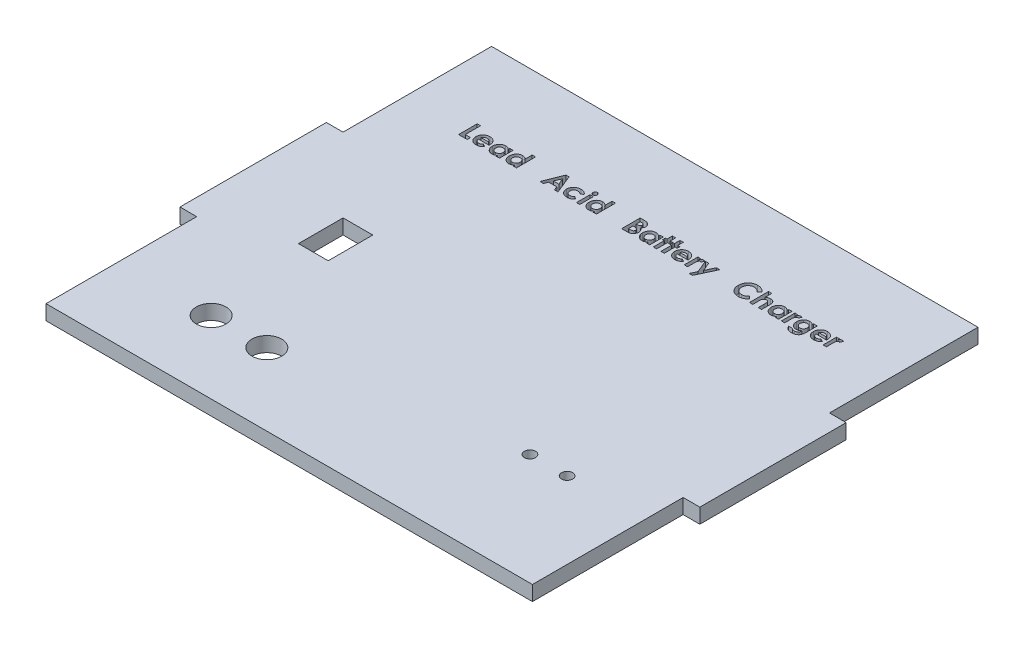
SolidWorks part; units mm, degrees
ref_plane "Front Plane" through (0, 0, 0) normal (0, 0, 1) x (1, 0, 0)
ref_plane "Top Plane" through (0, 0, 0) normal (0, 1, 0) x (1, 0, 0)
ref_plane "Right Plane" through (0, 0, 0) normal (1, 0, 0) x (0, 0, -1)
sketch "Sketch1" plane through (0, 0, 0) normal (0, 1, 0) x (1, 0, 0)
  line L0 (-65.5, 20) -> (-70, 20)
  line L1 (-65.5, -60) -> (65.5, -60)
  line L2 (-65.5, -60) -> (-65.5, -19.4155)
  line L3 (-65.5, 60) -> (65.5, 60)
  line L4 (65.5, -60) -> (65.5, -19.4155)
  line L5 (-65.5, -60) -> (65.5, 60) construction
  line L6 (-65.5, 60) -> (65.5, -60) construction
  line L7 (-70, 20) -> (-70, -19.4155)
  line L8 (-70, -19.4155) -> (-65.5, -19.4155)
  line L9 (-65.5, 20) -> (-65.5, 60)
  line L10 (0, 68.2418) -> (0, -80.8901) construction
  line L11 (70, -19.4155) -> (65.5, -19.4155)
  line L12 (70, 20) -> (70, -19.4155)
  line L13 (65.5, 20) -> (70, 20)
  line L14 (65.5, 20) -> (65.5, 60)
  point P1 (0, 0)
  dimension "D1" = 131
  dimension "D2" = 120
  dimension "D3" = 4.5
  dimension "D4" = 40
  dimension "D5" = 40.5845
extrude "Boss-Extrude1" add sketch "Sketch1" along normal blind 4
sketch "Sketch2" plane through (0, 4, 0) normal (0, 1, 0) x (1, 0, 0)
  line L0 (-65.5, -60) -> (65.5, -60) construction
  line L6 (-65.5, 20) -> (-70, 20) construction
  line L8 (-45.5, 0) -> (-37.5, 0)
  line L9 (-45.5, 0) -> (-45.5, -12)
  line L10 (-45.5, -12) -> (-37.5, -12)
  line L11 (-37.5, 0) -> (-37.5, -12)
  line L12 (-65.5, -19.4155) -> (-65.5, -60) construction
  circle A1 centre (34.8398, -30) radius 1.5
  circle A2 centre (44.8398, -30) radius 1.5
  circle A5 centre (-40.5, -40.5243) radius 4
  circle A6 centre (-25.5, -40.5243) radius 4
  point P22 (-41.5, 0)
  dimension "D1" = 30
  dimension "D5" = 8
  dimension "D7" = 8
  dimension "D2" = 10
  dimension "D3" = 8
  dimension "D4" = 12
  dimension "D6" = 20
  dimension "D8" = 20
  dimension "D9" = 25
  dimension "D10" = 15
extrude "Cut-Extrude1" cut sketch "Sketch2" against normal blind 10
sketch "Sketch3" plane through (0, 4, 0) normal (0, 1, 0) x (1, 0, 0)
  line L0 (-49.9553, 35) -> (52.1351, 35) construction
  line L1 (65.5, 60) -> (-65.5, 60) construction
  text T0 "<b>Lead   Acid   Battery   Charger</b>\r\n" font "Century Gothic" height 5
  point P5 (-53.9517, 35)
  point P6 (52.1351, 35)
  point P7 (-53.2251, 35)
  point P8 (-49.9553, 35)
  dimension "D1" = 25
extrude "Cut-Extrude3" cut sketch "Sketch3" against normal blind 2
